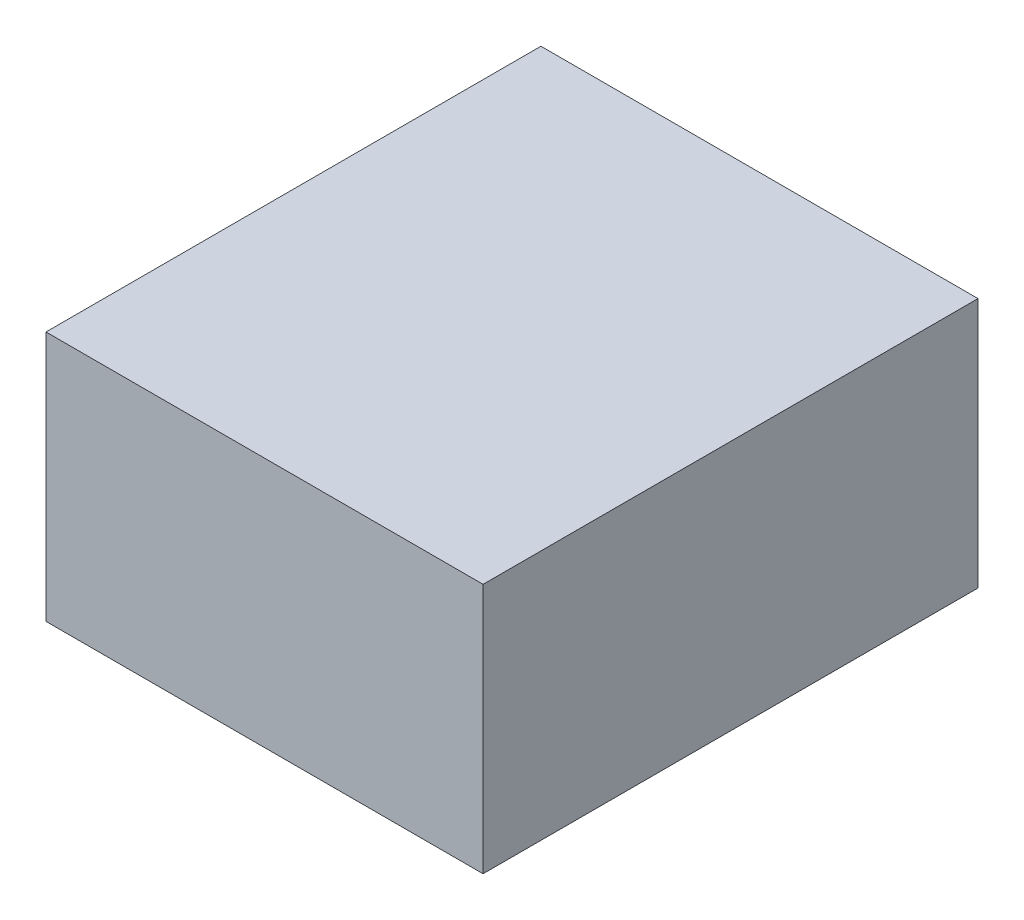
SolidWorks part; units mm, degrees
ref_plane "Front Plane" through (0, 0, 0) normal (0, 0, 1) x (1, 0, 0)
ref_plane "Top Plane" through (0, 0, 0) normal (0, 1, 0) x (1, 0, 0)
ref_plane "Right Plane" through (0, 0, 0) normal (1, 0, 0) x (0, 0, -1)
sketch "Sketch1" plane through (0, 0, 0) normal (0, 0, 1) x (1, 0, 0)
  line L1 (-34, -19.5) -> (34, -19.5)
  line L2 (-34, -19.5) -> (-34, 19.5)
  line L3 (-34, 19.5) -> (34, 19.5)
  line L4 (34, -19.5) -> (34, 19.5)
  line L5 (-34, -19.5) -> (34, 19.5) construction
  line L6 (-34, 19.5) -> (34, -19.5) construction
  point P0 (0, 0)
  dimension "D1" = 39
  dimension "D2" = 68
extrude "Boss-Extrude1" add sketch "Sketch1" along normal mid plane 77
